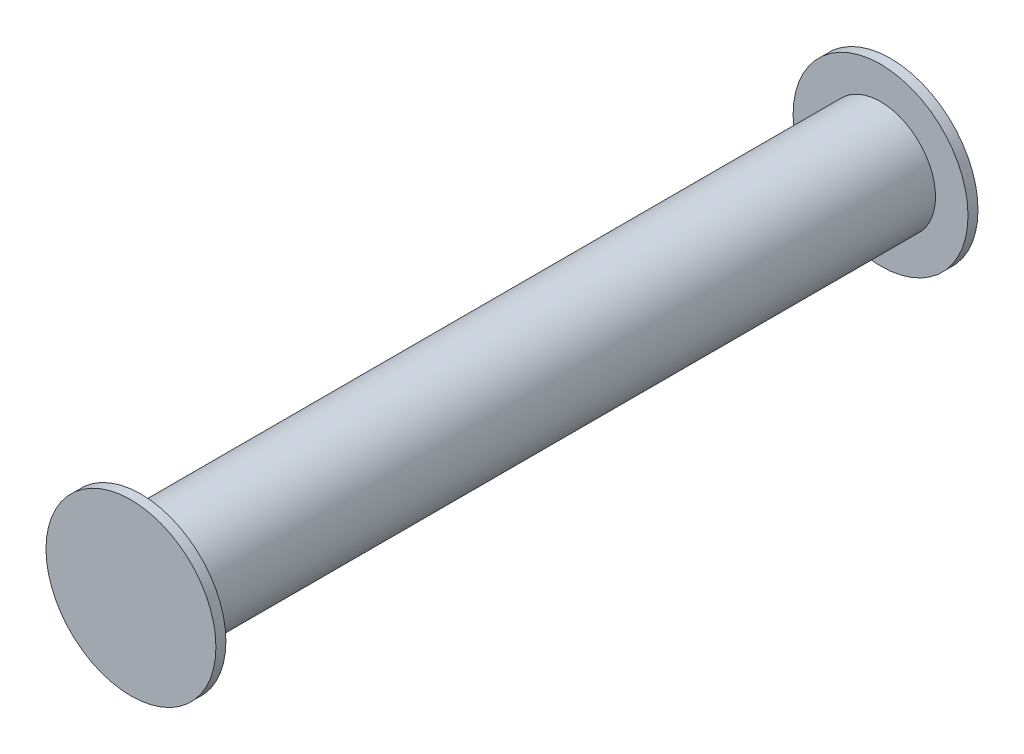
SolidWorks part; units mm, degrees
ref_plane "Plan de face" through (0, 0, 0) normal (0, 0, 1) x (1, 0, 0)
ref_plane "Plan de dessus" through (0, 0, 0) normal (0, 1, 0) x (1, 0, 0)
ref_plane "Plan de droite" through (0, 0, 0) normal (1, 0, 0) x (0, 0, -1)
sketch "Esquisse1" plane through (0, 0, 0) normal (0, 0, 1) x (1, 0, 0)
  circle A0 centre (0, 0) radius 17.5
  dimension "D1" = 35
extrude "Boss.-Extru.1" add sketch "Esquisse1" along normal blind 2
sketch "Esquisse2" plane through (0, 0, 2) normal (0, 0, 1) x (1, 0, 0)
  circle A0 centre (0, 0) radius 11
  dimension "D1" = 22
extrude "Boss.-Extru.2" add sketch "Esquisse2" along normal blind 150
sketch "Esquisse3" plane through (0, 0, 0) normal (0, 1, 0) x (1, 0, 0)
  line L0 (0, -137.2202) -> (0, -161.9194) construction
  line L1 (11, -152) -> (17, -152)
  line L2 (11, -152) -> (11, -150)
  line L3 (11, -150) -> (17, -150)
  line L4 (17, -152) -> (17, -150)
  dimension "D1" = 2
  dimension "D2" = 6
revolve "Révolution1" add sketch "Esquisse3" angle 360 about L0
